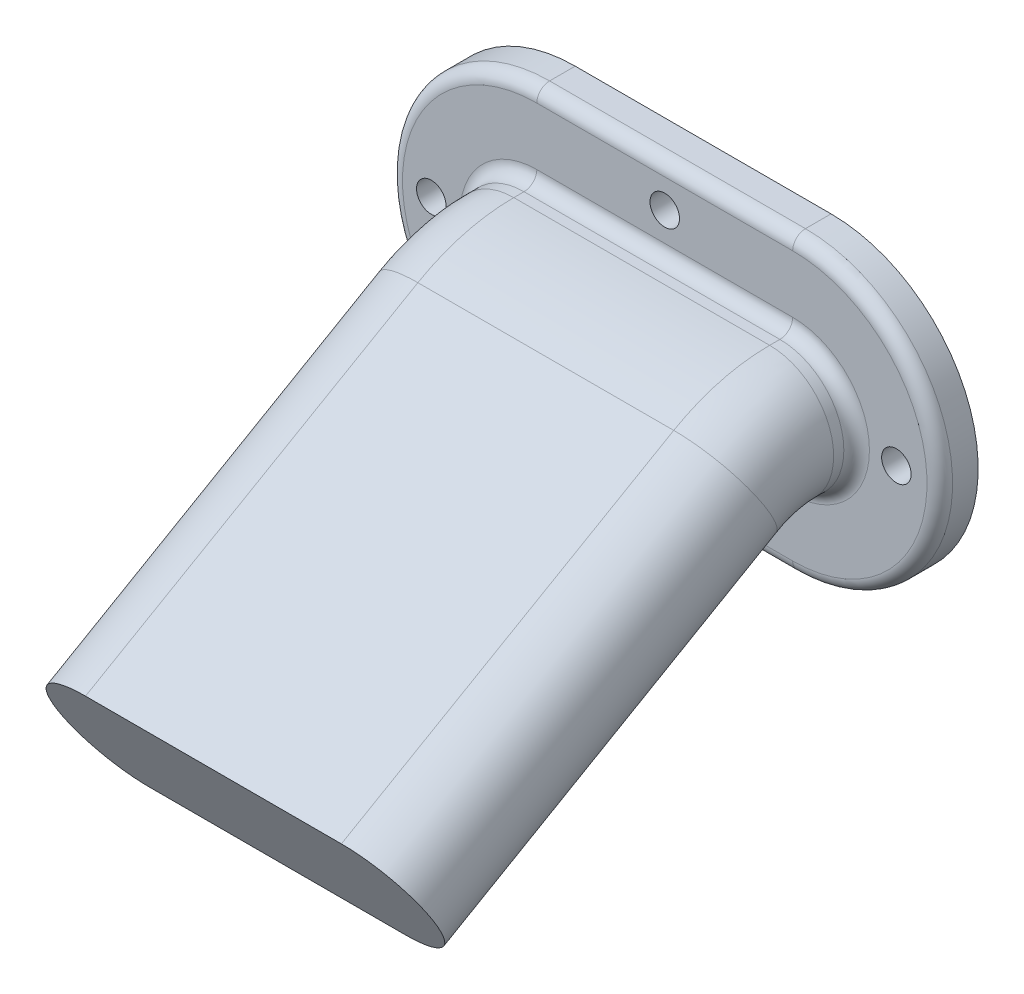
SolidWorks part; units mm, degrees
ref_plane "Front Plane" through (0, 0, 0) normal (0, 0, 1) x (1, 0, 0)
ref_plane "Top Plane" through (0, 0, 0) normal (0, 1, 0) x (1, 0, 0)
ref_plane "Right Plane" through (0, 0, 0) normal (1, 0, 0) x (0, 0, -1)
sketch "Sketch1" plane through (0, 0, 0) normal (1, 0, 0) x (0, 0, -1)
  line L0 (0, 0) -> (65.9911, 38.1)
  line L1 (78.6911, 41.503) -> (90.8788, 41.503)
  arc A0 (65.9911, 38.1) -> (78.6911, 41.503) centre (78.6911, 16.103) cw
  dimension "D2" = 25.4
  dimension "D1" = 30
  dimension "D3" = 76.2
ref_plane "Plane1" through (0, 0, 0) normal (0, 0.5, -0.866) x (-1, 0, 0)
sketch "Sketch2" plane through (0, 0, 0) normal (0, 0.5, -0.866) x (-1, 0, 0)
  line L1 (-25.4, 12.7) -> (25.4, 12.7)
  line L3 (-25.4, -12.7) -> (25.4, -12.7)
  arc A0 (25.4, -12.7) -> (25.4, 12.7) centre (25.4, 0) ccw
  arc A1 (-25.4, 12.7) -> (-25.4, -12.7) centre (-25.4, 0) ccw
  point P0 (0, 0)
  dimension "D1" = 50.8
  dimension "D2" = 25.4
sweep "Sweep5" add profiles "Sketch2" path "Sketch1"
ref_plane "Plane6" through (0, 0, -90.8788) normal (0, 0, -1) x (-1, 0, 0)
sketch "Sketch9" plane through (0, 0, -90.8788) normal (0, 0, -1) x (-1, 0, 0)
  line L0 (-25.4, 54.203) -> (25.4, 54.203)
  line L1 (-25.4, 28.803) -> (25.4, 28.803)
  line L2 (-25.4, 70.713) -> (25.4, 70.713)
  line L3 (-25.4, 12.293) -> (25.4, 12.293)
  line L5 (-25.4, 62.458) -> (25.4, 62.458) construction
  line L6 (-25.4, 20.548) -> (25.4, 20.548) construction
  arc A0 (25.4, 28.803) -> (25.4, 54.203) centre (25.4, 41.503) ccw
  arc A1 (-25.4, 28.803) -> (-25.4, 54.203) centre (-25.4, 41.503) cw
  arc A2 (25.4, 12.293) -> (25.4, 70.713) centre (25.4, 41.503) ccw
  arc A3 (-25.4, 12.293) -> (-25.4, 70.713) centre (-25.4, 41.503) cw
  circle A4 centre (-45.991, 41.503) radius 2.9288
  arc A5 (25.4, 20.548) -> (25.4, 62.458) centre (25.4, 41.503) ccw construction
  arc A6 (-25.4, 20.548) -> (-25.4, 62.458) centre (-25.4, 41.503) cw construction
  circle A7 centre (0, 62.458) radius 2.9288
  circle A8 centre (46.355, 41.503) radius 2.9288
  circle A9 centre (0, 20.548) radius 2.9288
  dimension "D1" = 16.51
  dimension "D2" = 8.255
extrude "Extrude2" add sketch "Sketch9" against normal blind 7.62
fillet "Fillet3" radius 2.54 8 edges at (-54.61, 41.503, -83.2588) (0, 12.293, -83.2588) (54.61, 41.503, -83.2588) (-38.1, 41.503, -83.2588) (0, 28.803, -83.2588) (38.1, 41.503, -83.2588) (0, 70.713, -83.2588) (0, 54.203, -83.2588)
